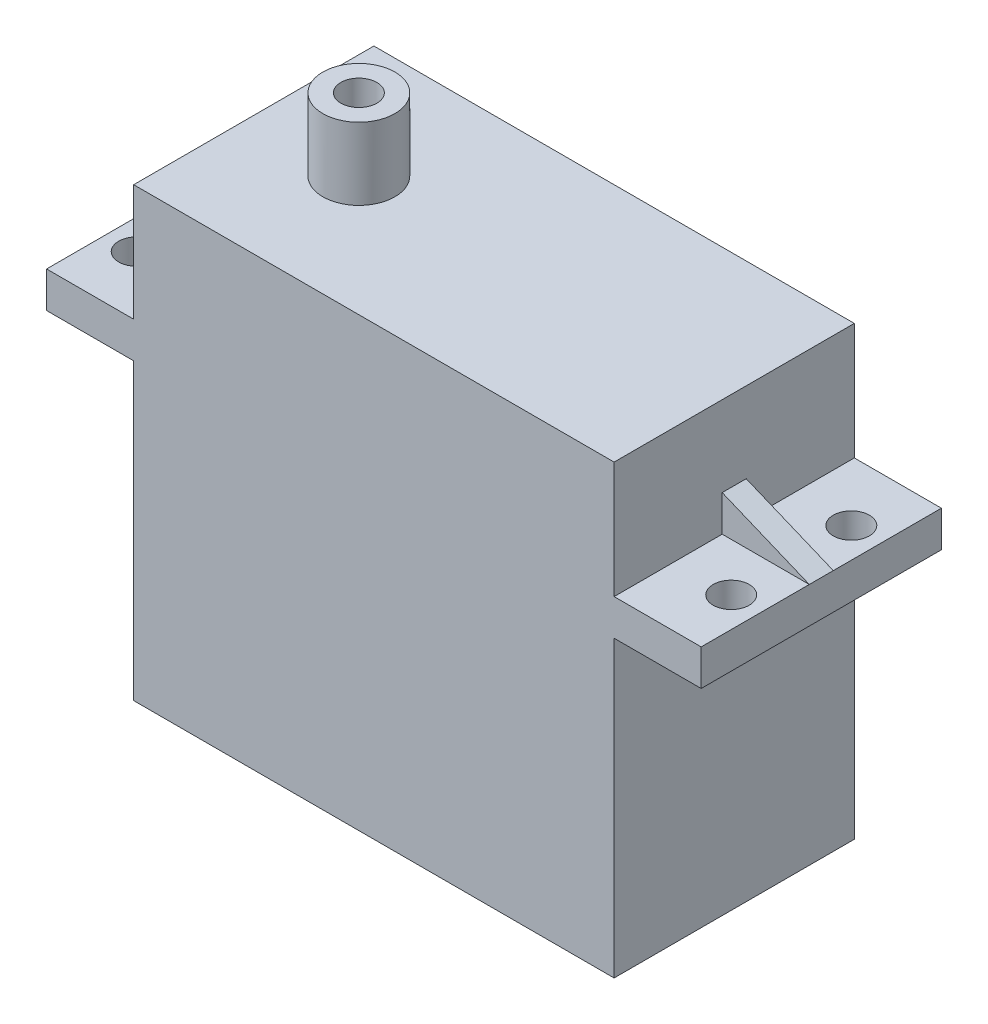
SolidWorks part; units mm, degrees
ref_plane "前视基准面" through (0, 0, 0) normal (0, 0, 1) x (1, 0, 0)
ref_plane "上视基准面" through (0, 0, 0) normal (0, 1, 0) x (1, 0, 0)
ref_plane "右视基准面" through (0, 0, 0) normal (1, 0, 0) x (0, 0, -1)
other "Configuration Table"
sketch "草图1" plane through (0, 0, 0) normal (0, 1, 0) x (1, 0, 0)
  line L1 (20, 10) -> (-20, 10)
  line L2 (20, 10) -> (20, -10)
  line L3 (20, -10) -> (-20, -10)
  line L4 (-20, 10) -> (-20, -10)
  line L5 (20, 10) -> (-20, -10) construction
  line L6 (20, -10) -> (-20, 10) construction
  point P0 (0, 0)
  dimension "D1" = 20
  dimension "D2" = 40
extrude "凸台-拉伸1" add sketch "草图1" along normal blind 37.2
ref_plane "基准面1" through (0, 24.5, 0) normal (0, -1, 0) x (-1, 0, 0)
sketch "草图2" plane through (0, 24.5, 0) normal (0, -1, 0) x (-1, 0, 0)
  line L0 (20, -10) -> (-20, -10) construction
  line L1 (27.25, 10) -> (-27.25, 10)
  line L2 (27.25, 10) -> (27.25, -10)
  line L3 (27.25, -10) -> (-27.25, -10)
  line L4 (-27.25, 10) -> (-27.25, -10)
  line L5 (27.25, 10) -> (-27.25, -10) construction
  line L6 (27.25, -10) -> (-27.25, 10) construction
  line L8 (24.75, 5) -> (-24.75, 5) construction
  line L9 (24.75, 5) -> (24.75, -5) construction
  line L10 (24.75, -5) -> (-24.75, -5) construction
  line L11 (-24.75, 5) -> (-24.75, -5) construction
  line L12 (24.75, 5) -> (-24.75, -5) construction
  line L13 (24.75, -5) -> (-24.75, 5) construction
  circle A0 centre (-24.75, 5) radius 1.5
  circle A1 centre (-24.75, -5) radius 1.5
  circle A2 centre (24.75, -5) radius 1.5
  circle A3 centre (24.75, 5) radius 1.5
  point P0 (0, 0)
  point P8 (0, 0)
  dimension "D4" = 3
  dimension "D1" = 54.5
  dimension "D2" = 10
  dimension "D3" = 49.5
extrude "凸台-拉伸2" add sketch "草图2" against normal blind 3
sketch "草图3" plane through (0, 37.2, 0) normal (0, 1, 0) x (1, 0, 0)
  line L0 (-27.25, 0) -> (-11.25, 0) construction
  line L1 (-27.25, -10) -> (-27.25, 10) construction
  circle A0 centre (-11.25, 0) radius 3
  circle A1 centre (-11.25, 0) radius 1.5
  dimension "D1" = 3
  dimension "D2" = 6
  dimension "D3" = 16
extrude "凸台-拉伸3" add sketch "草图3" along normal blind 6
sketch "草图4" plane through (-20, 0, 0) normal (-1, 0, 0) x (0, 0, 1)
  line L0 (0, 0) -> (0, 50000) construction
  line L1 (-10, 0) -> (10, 0) construction
  line L2 (3.5633, 2.0788) -> (-3.5633, 2.0788)
  line L3 (3.5633, 2.0788) -> (3.5633, 0)
  line L4 (3.5633, 0) -> (-3.5633, 0)
  line L5 (-3.5633, 2.0788) -> (-3.5633, 0)
  line L6 (3.5633, 2.0788) -> (-3.5633, 0) construction
  line L7 (3.5633, 0) -> (-3.5633, 2.0788) construction
  point P3 (0, 1.0394)
extrude "凸台-拉伸4" add sketch "草图4" along normal blind 3
sketch "草图5" plane through (0, 0, 0) normal (0, 0, 1) x (1, 0, 0)
  line L0 (-27.25, 27.5) -> (-20, 30.5)
  line L1 (-20, 30.5) -> (-20, 27.5)
  line L2 (-20, 27.5) -> (-27.25, 27.5)
  line L3 (20, 27.5) -> (27.25, 27.5)
  line L4 (27.25, 27.5) -> (20, 30.5)
  line L5 (20, 37.2) -> (20, 27.5) construction
  line L6 (20, 30.5) -> (20, 27.5)
  line L7 (-20, 37.2) -> (-20, 27.5) construction
  dimension "D1" = 3
  dimension "D2" = 3
extrude "凸台-拉伸5" add sketch "草图5" along normal mid plane 2
